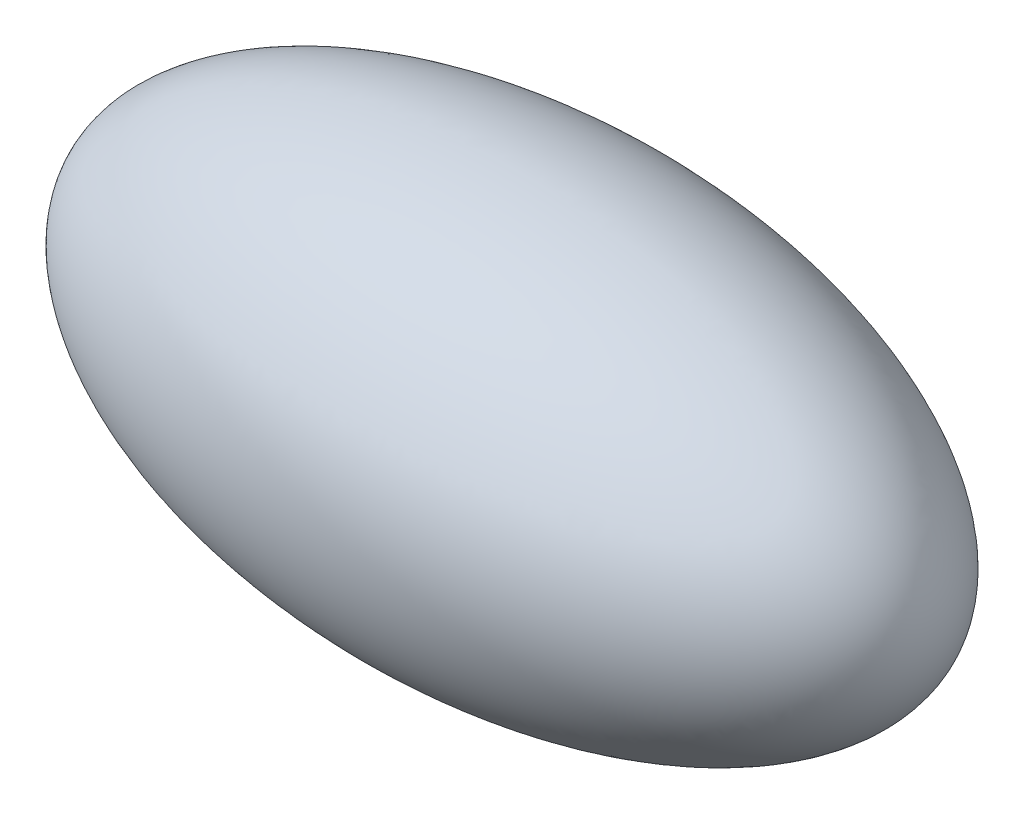
SolidWorks part; units mm, degrees
material "ABS"
ref_plane "Front Plane" through (0, 0, 0) normal (0, 0, 1) x (1, 0, 0)
ref_plane "Top Plane" through (0, 0, 0) normal (0, 1, 0) x (1, 0, 0)
ref_plane "Right Plane" through (0, 0, 0) normal (1, 0, 0) x (0, 0, -1)
sketch "Sketch2" plane through (0, 0, 0) normal (0, 0, 1) x (1, 0, 0)
  line L0 (0, 0) -> (0, 25) construction
  line L1 (0, 25) -> (50, 0) construction
  line L2 (50, 0) -> (0, 0) construction
  line L3 (0, 0) -> (-50, 0) construction
  line L4 (0, 25) -> (-50, 25) construction
  line L5 (-50, 25) -> (-50, 0) construction
  line L6 (-50, 25) -> (50, 25)
  ellipse E0 centre (0, 25) end of major axis (50, 25) minor radius 25 (-50, 25) -> (50, 25) ccw
  dimension "D1" = 25
  dimension "D2" = 50
  dimension "D3" = 50
revolve "Revolve1" add sketch "Sketch2" angle 360 about L6
